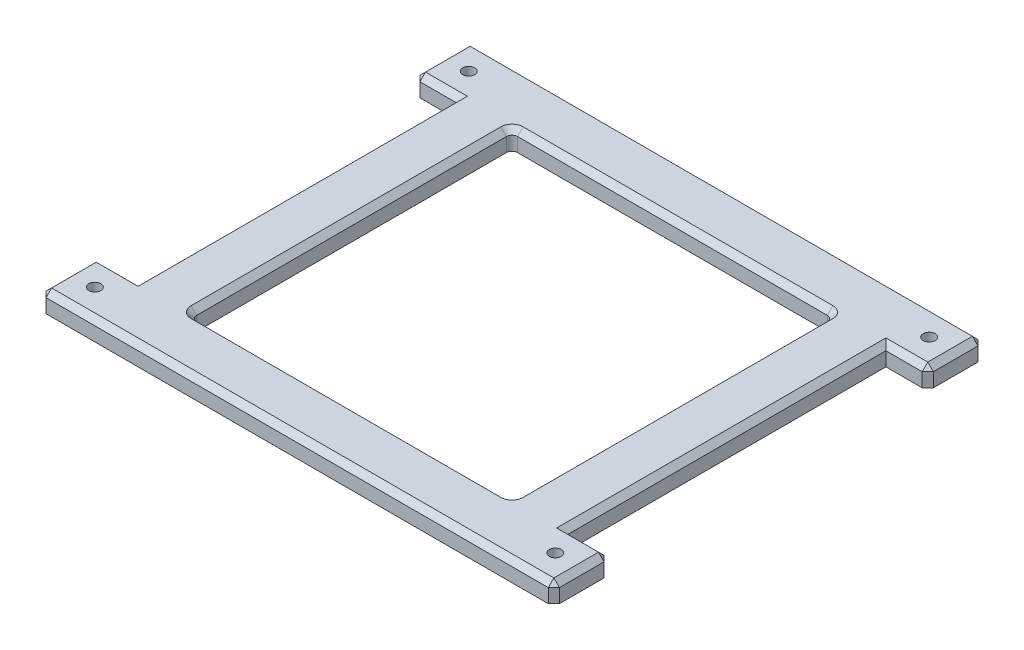
SolidWorks part; units mm, degrees
ref_plane "Спереди" through (0, 0, 0) normal (0, 0, 1) x (1, 0, 0)
ref_plane "Сверху" through (0, 0, 0) normal (0, 1, 0) x (1, 0, 0)
ref_plane "Справа" through (0, 0, 0) normal (1, 0, 0) x (0, 0, -1)
sketch "Эскиз1" plane through (0, 0, 0) normal (0, 1, 0) x (1, 0, 0)
  line L1 (-77, -77) -> (77, -77)
  line L2 (-77, -77) -> (-77, 77)
  line L3 (-77, 77) -> (77, 77)
  line L4 (77, -77) -> (77, 77)
  line L5 (-77, -77) -> (77, 77) construction
  line L6 (-77, 77) -> (77, -77) construction
  point P0 (0, 0)
  dimension "D1" = 154
extrude "Бобышка-Вытянуть1" add sketch "Эскиз1" along normal blind 7
sketch "Эскиз7" plane through (0, 0, 0) normal (0, -1, 0) x (1, 0, 0)
  line L0 (-62.25, -64.75) -> (-62.25, -69.75) construction
  line L1 (-62.25, -69.75) -> (-72.25, -69.75) construction
  line L2 (-72.25, -69.75) -> (-72.25, -64.75) construction
  line L3 (-72.25, -64.75) -> (-62.25, -64.75) construction
  line L4 (72.25, -64.75) -> (72.25, -69.75) construction
  line L5 (62.25, -64.75) -> (72.25, -64.75) construction
  line L6 (62.25, -69.75) -> (62.25, -64.75) construction
  line L7 (72.25, -69.75) -> (62.25, -69.75) construction
  line L8 (72.25, 69.75) -> (72.25, 64.75) construction
  line L9 (72.25, 64.75) -> (62.25, 64.75) construction
  line L10 (62.25, 64.75) -> (62.25, 69.75) construction
  line L11 (62.25, 69.75) -> (72.25, 69.75) construction
  line L12 (-62.25, 69.75) -> (-62.25, 64.75) construction
  line L13 (-62.25, 64.75) -> (-72.25, 64.75) construction
  line L14 (-72.25, 64.75) -> (-72.25, 69.75) construction
  line L15 (-72.25, 69.75) -> (-62.25, 69.75) construction
  line L16 (-62.25, -64.75) -> (-62.25, -69.75) construction
  line L17 (-62.25, -69.75) -> (-72.25, -69.75) construction
  line L18 (-72.25, -69.75) -> (-72.25, -64.75) construction
  line L19 (-72.25, -64.75) -> (-62.25, -64.75) construction
  line L20 (72.25, -64.75) -> (72.25, -69.75) construction
  line L21 (62.25, -64.75) -> (72.25, -64.75) construction
  line L22 (62.25, -69.75) -> (62.25, -64.75) construction
  line L23 (72.25, -69.75) -> (62.25, -69.75) construction
  line L24 (72.25, 69.75) -> (72.25, 64.75) construction
  line L25 (72.25, 64.75) -> (62.25, 64.75) construction
  line L26 (62.25, 64.75) -> (62.25, 69.75) construction
  line L27 (62.25, 69.75) -> (72.25, 69.75) construction
  line L28 (-62.25, 69.75) -> (-62.25, 64.75) construction
  line L29 (-62.25, 64.75) -> (-72.25, 64.75) construction
  line L30 (-72.25, 64.75) -> (-72.25, 69.75) construction
  line L31 (-72.25, 69.75) -> (-62.25, 69.75) construction
  line L32 (-61.95, 70.05) -> (-61.95, 64.45)
  line L33 (-61.95, 64.45) -> (-72.55, 64.45)
  line L34 (-72.55, 64.45) -> (-72.55, 70.05)
  line L35 (-72.55, 70.05) -> (-61.95, 70.05)
  line L36 (72.55, 70.05) -> (72.55, 64.45)
  line L37 (72.55, 64.45) -> (61.95, 64.45)
  line L38 (61.95, 64.45) -> (61.95, 70.05)
  line L39 (61.95, 70.05) -> (72.55, 70.05)
  line L40 (-61.95, -64.45) -> (-61.95, -70.05)
  line L41 (-61.95, -70.05) -> (-72.55, -70.05)
  line L42 (-72.55, -70.05) -> (-72.55, -64.45)
  line L43 (-72.55, -64.45) -> (-61.95, -64.45)
  line L44 (72.55, -64.45) -> (72.55, -70.05)
  line L45 (72.55, -70.05) -> (61.95, -70.05)
  line L46 (61.95, -70.05) -> (61.95, -64.45)
  line L47 (61.95, -64.45) -> (72.55, -64.45)
  dimension "D1" = 0.3
  dimension "D2" = 0.3
  dimension "D3" = 0.3
  dimension "D4" = 0.3
extrude "Вырез-Вытянуть2" cut sketch "Эскиз7" against normal blind 2
sketch "Эскиз8" plane through (0, 7, 0) normal (0, 1, 0) x (1, 0, 0)
  line L1 (-57.5, -57.5) -> (57.5, -57.5)
  line L2 (-57.5, -57.5) -> (-57.5, 57.5)
  line L3 (-57.5, 57.5) -> (57.5, 57.5)
  line L4 (57.5, -57.5) -> (57.5, 57.5)
  line L5 (-57.5, -57.5) -> (57.5, 57.5) construction
  line L6 (-57.5, 57.5) -> (57.5, -57.5) construction
  point P0 (0, 0)
  dimension "D1" = 115
extrude "Вырез-Вытянуть3" cut sketch "Эскиз8" against normal through all
sketch "Эскиз11" plane through (77, 0, 0) normal (1, 0, 0) x (0, 0, -1)
  line L0 (-77, 0) -> (-77, 7)
  line L1 (-77, 0) -> (-57, 0)
  line L2 (-77, 7) -> (-57, 7)
  line L3 (-57, 0) -> (-57, 7)
  dimension "D1" = 20
extrude "Бобышка-Вытянуть6" add sketch "Эскиз11" along normal blind 15
mirror "Зеркальное отражение5" about plane through (0, 0, 0) normal (0, 0, 1) of "Бобышка-Вытянуть6"
mirror "Зеркальное отражение6" about plane through (0, 0, 0) normal (1, 0, 0) of "Бобышка-Вытянуть6", "Зеркальное отражение5"
fillet "Скругление6" radius 2 4 edges at (57.5, 3.5, -57.5) (57.5, 3.5, 57.5) (-57.5, 3.5, -57.5) (-57.5, 3.5, 57.5)
fillet "Скругление5" radius 2 28 edges at (84.5, 7, -57) (92, 7, -67) (-84.5, 7, -57) (-92, 7, -67) (0, 7, -77) (0, 7, -57.5) (-57.5, 7, 0) (0, 7, 57.5) (57.5, 7, 0) (77, 7, 0) (84.5, 7, 57) (92, 7, 67) (0, 7, 77) (-92, 7, 67) (-84.5, 7, 57) (-77, 7, 0) (56.9142, 7, 56.9142) (-56.9142, 7, 56.9142) (-56.9142, 7, -56.9142) (56.9142, 7, -56.9142) (-92, 3.5, 77) (-92, 3.5, 57) (-92, 3.5, -57) (-92, 3.5, -77) (92, 3.5, 57) (92, 3.5, -57) (92, 3.5, -77) (92, 3.5, 77) profile chamfer
hole_wizard "Сверло под метчик  спиральное M31" positions "Эскиз12" profile "Эскиз13" hole size "M3x0.5" standard "DIN" end condition through all
sketch "Эскиз12" plane through (0, 7, 0) normal (0, 1, 0) x (1, 0, 0)
  line L0 (-90, 67) -> (-75, 67) construction
  line L1 (-90, 75) -> (-90, 59) construction
  line L2 (-75, 75) -> (-75, -75) construction
  line L5 (90, 67) -> (75, 67) construction
  line L6 (90, 59) -> (90, 75) construction
  line L7 (75, -75) -> (75, 75) construction
  line L10 (90, -67) -> (75, -67) construction
  line L11 (90, -75) -> (90, -59) construction
  line L13 (-90, -67) -> (-75, -67) construction
  line L14 (-90, -59) -> (-90, -75) construction
  point P33 (-82.5, 67)
  point P34 (82.5, 67)
  point P37 (-82.5, -67)
  point P39 (82.5, -67)
sketch "Эскиз13" plane through (82.5, 7, 67) normal (1, 0, 0) x (0, 0, 1)
  line L0 (0, 0) -> (0, 7)
  line L1 (0, 7) -> (1.575, 7)
  line L2 (1.575, 7) -> (1.575, 0)
  line L5 (1.575, 0) -> (0, 0)
  line L11 (0, -6.35) -> (0, 107.95) construction
  dimension "Диаметр сквозного отверстия" = 3.15
  dimension "Глубина сквозного отверстия" = 7
sketch "Эскиз14" plane through (0, 7, 0) normal (0, 1, 0) x (1, 0, 0)
  circle A0 centre (-82.5, 67) radius 2.15
  circle A1 centre (82.5, 67) radius 2.15
  circle A2 centre (-82.5, -67) radius 2.15
  circle A3 centre (82.5, -67) radius 2.15
  dimension "D1" = 4.3
extrude "Вырез-Вытянуть4" cut sketch "Эскиз14" against normal blind 5
